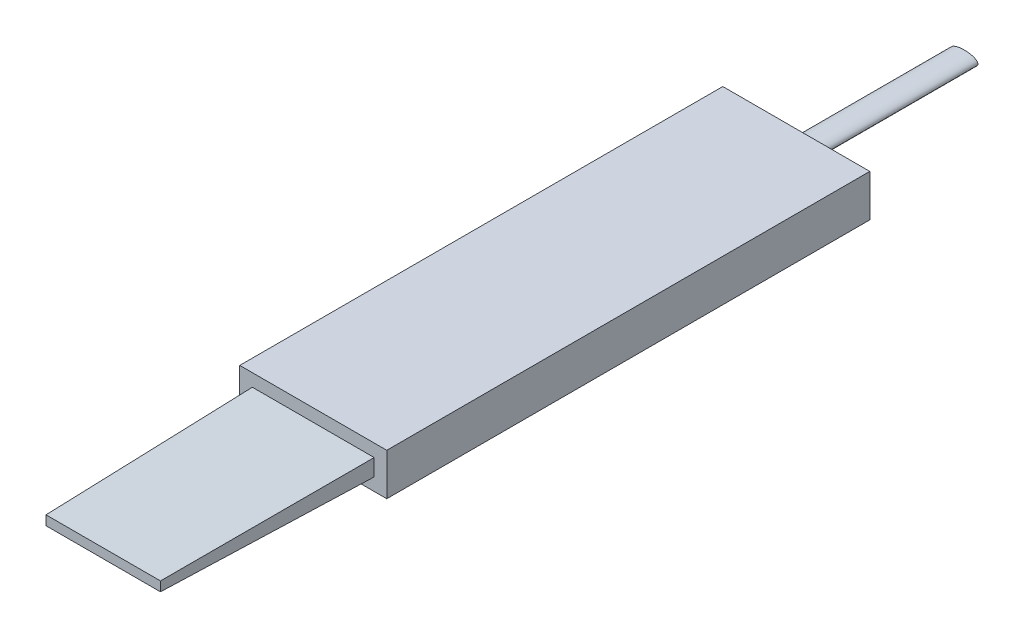
SolidWorks part; units mm, degrees
ref_plane "Front Plane" through (0, 0, 0) normal (0, 0, 1) x (1, 0, 0)
ref_plane "Top Plane" through (0, 0, 0) normal (0, 1, 0) x (1, 0, 0)
ref_plane "Right Plane" through (0, 0, 0) normal (1, 0, 0) x (0, 0, -1)
sketch "Sketch1" plane through (0, 0, 0) normal (0, 1, 0) x (1, 0, 0)
  line L1 (-42.0732, 35.4268) -> (-7.0732, 35.4268)
  line L2 (-42.0732, 35.4268) -> (-42.0732, -79.5732)
  line L3 (-42.0732, -79.5732) -> (-7.0732, -79.5732)
  line L4 (-7.0732, 35.4268) -> (-7.0732, -79.5732)
  line L5 (-42.0732, 35.4268) -> (-7.0732, -79.5732) construction
  line L6 (-42.0732, -79.5732) -> (-7.0732, 35.4268) construction
  point P4 (-24.5732, -22.0732)
  dimension "D1" = 35
  dimension "D2" = 115
extrude "Boss-Extrude1" add sketch "Sketch1" along normal blind 10
sketch "Sketch2" plane through (0, 0, 79.5732) normal (0, 0, 1) x (1, 0, 0)
  line L0 (-39.0732, 3) -> (-10.0732, 3)
  line L1 (-10.0732, 3) -> (-10.0732, 7)
  line L2 (-10.0732, 7) -> (-39.0732, 7)
  line L3 (-39.0732, 7) -> (-39.0732, 3)
extrude "Boss-Extrude2" add sketch "Sketch2" along normal blind 50 draft 1 contours L0 L1 L2 L3
sketch "Sketch3" plane through (0, 0, -35.4268) normal (0, 0, -1) x (-1, 0, 0)
  ellipse E0 centre (24.5732, 5) end of major axis (27.8331, 5) minor radius 1.2797
extrude "Boss-Extrude3" add sketch "Sketch3" along normal blind 40
